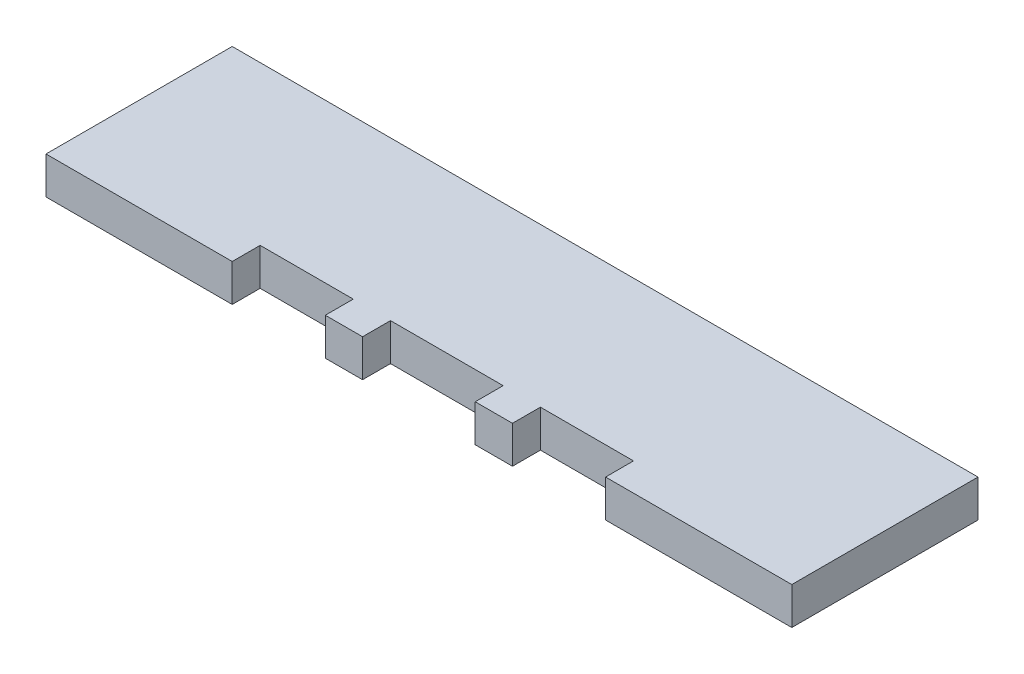
SolidWorks part; units mm, degrees
ref_plane "Спереди" through (0, 0, 0) normal (0, 0, 1) x (1, 0, 0)
ref_plane "Сверху" through (0, 0, 0) normal (0, 1, 0) x (1, 0, 0)
ref_plane "Справа" through (0, 0, 0) normal (1, 0, 0) x (0, 0, -1)
other "Configuration Table"
sketch "Эскиз1" plane through (0, 0, 0) normal (0, 1, 0) x (1, 0, 0)
  line L0 (0, 0) -> (0, 3)
  line L1 (0, 3) -> (40.1, 3)
  line L2 (40.1, 3) -> (40.1, 0)
  line L3 (40.1, 0) -> (60.1, 0)
  line L4 (60.1, 0) -> (60.1, 20)
  line L5 (60.1, 20) -> (-20, 20)
  line L6 (-20, 20) -> (-20, 0)
  line L7 (-20, 0) -> (0, 0)
  dimension "D1" = 40.1
  dimension "D2" = 3
  dimension "D3" = 20
  dimension "D4" = 20
  dimension "D5" = 20
extrude "Бобышка-Вытянуть1" add sketch "Эскиз1" along normal blind 4
sketch "Эскиз2" plane through (0, 0, -3) normal (0, 0, 1) x (1, 0, 0)
  line L0 (0, 4) -> (40.1, 4) construction
  line L1 (26.1, 4) -> (30.1, 4)
  line L2 (26.1, 4) -> (26.1, 0)
  line L3 (26.1, 0) -> (30.1, 0)
  line L4 (30.1, 4) -> (30.1, 0)
  line L5 (0, 0) -> (40.1, 0) construction
  line L7 (40.1, 4) -> (40.1, 0) construction
  line L8 (10, 4) -> (10, 0)
  line L9 (10, 4) -> (14, 4)
  line L10 (14, 4) -> (14, 0)
  line L11 (10, 0) -> (14, 0)
  line L12 (0, 4) -> (0, 0) construction
  dimension "D1" = 4
  dimension "D2" = 10
  dimension "D3" = 2
  dimension "D4" = 10
extrude "Бобышка-Вытянуть3" add sketch "Эскиз2" along normal blind 3
sketch "Эскиз4" plane through (0, 0, 0) normal (0, 0, 1) x (1, 0, 0)
  line L0 (0, 0) -> (-1.147, 4)
  line L1 (-20, 4) -> (0, 4) construction
  line L2 (-1.147, 4) -> (0, 4)
  line L3 (0, 4) -> (0, 0)
  line L4 (40.1, 4) -> (41.247, 0)
  line L5 (40.1, 0) -> (60.1, 0) construction
  line L6 (41.247, 0) -> (40.1, 0)
  line L7 (40.1, 0) -> (40.1, 4)
  dimension "D1" = 16
  dimension "D2" = 16
